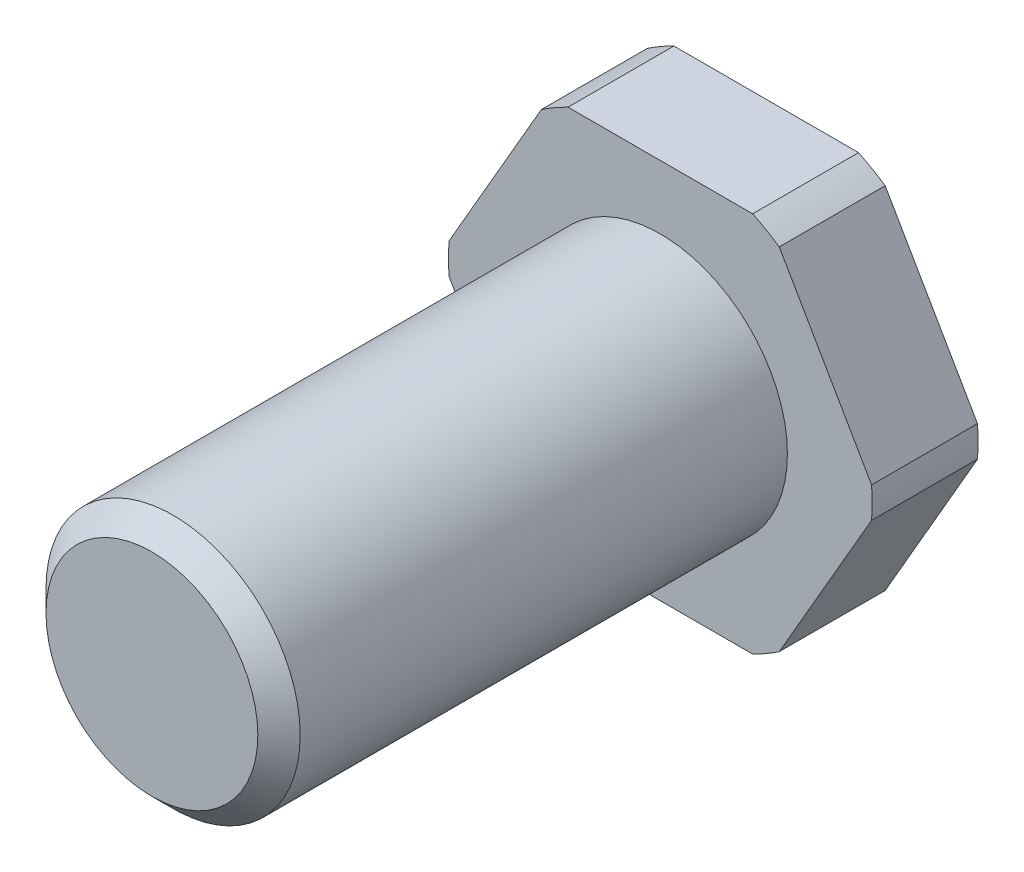
SolidWorks part; units mm, degrees
ref_plane "前视基准面" through (0, 0, 0) normal (0, 0, 1) x (1, 0, 0)
ref_plane "上视基准面" through (0, 0, 0) normal (0, 1, 0) x (1, 0, 0)
ref_plane "右视基准面" through (0, 0, 0) normal (1, 0, 0) x (0, 0, -1)
sketch "草图1" plane through (0, 0, 0) normal (0, 0, 1) x (1, 0, 0)
  line L1 (10.3923, 0) -> (5.1962, 9)
  line L2 (5.1962, 9) -> (-5.1962, 9)
  line L3 (-5.1962, 9) -> (-10.3923, 0)
  line L4 (-10.3923, 0) -> (-5.1962, -9)
  line L5 (-5.1962, -9) -> (5.1962, -9)
  line L6 (5.1962, -9) -> (10.3923, 0)
  circle A0 centre (0, 0) radius 9 construction
  dimension "D1" = 18
extrude "凸台-拉伸1" add sketch "草图1" along normal blind 5
sketch "草图2" plane through (0, 0, 5) normal (0, 0, 1) x (1, 0, 0)
  circle A0 centre (0, 0) radius 6
  dimension "D1" = 12
extrude "凸台-拉伸2" add sketch "草图2" along normal blind 24
cosmetic thread "装饰螺纹线1" parameters "D2"=11
hole_wizard "M8x1.25 螺纹孔1" positions "草图4" profile "草图3" tap size "M8x1.25" standard "JIS"
sketch "草图4" plane through (-3.3513, -2.4615, 0) normal (0, 0, 1) x (1, 0, 0)
  point P1 (3.3513, 2.4615)
cosmetic thread "孔螺蚊线1" parameters "D1"=15, "D2"=8
sketch "草图3" plane through (0, 0, 0) normal (1, 0, 0) x (0, 1, 0)
  line L0 (0, 0) -> (0, 17.0429)
  line L1 (0, 17.0429) -> (3.4, 15)
  line L2 (3.4, 15) -> (3.4, 0)
  line L5 (3.4, 0) -> (0, 0)
  line L10 (0, 17.0429) -> (-3.4, 15) construction
  line L11 (0, -6.35) -> (0, 107.95) construction
  dimension "螺纹孔钻头直径" = 6.8
  dimension "螺纹孔钻头深度" = 15
  dimension "导头角度" = 118
sketch "草图5" plane through (0, 0, 5) normal (0, 0, 1) x (1, 0, 0)
  circle A0 centre (0, 0) radius 10
  dimension "D1" = 20
extrude "切除-拉伸1" cut sketch "草图5" against normal through all flip side to cut
chamfer "倒角1" distance 1 angle 45 1 edges at (6, 0, 29)
